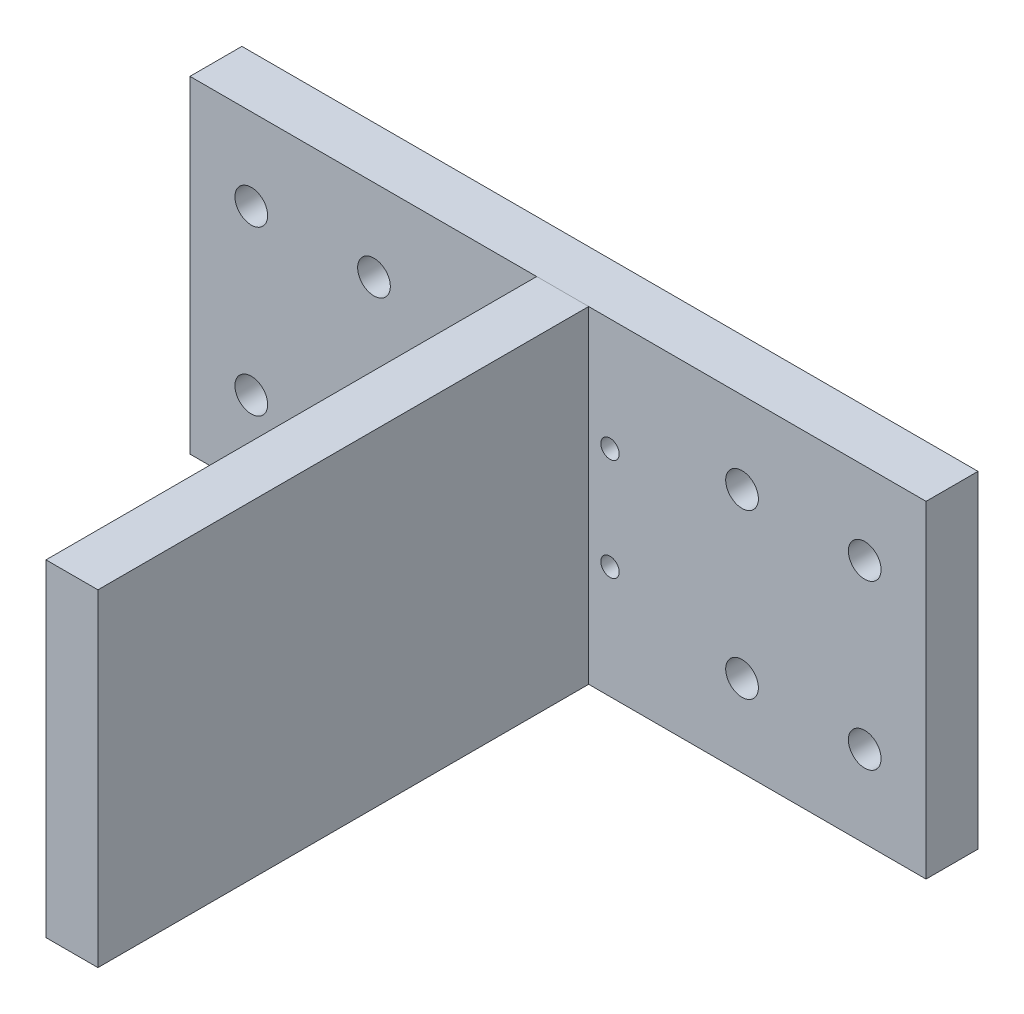
SolidWorks part; units mm, degrees
ref_plane "Alzado" through (0, 0, 0) normal (0, 0, 1) x (1, 0, 0)
ref_plane "Planta" through (0, 0, 0) normal (0, 1, 0) x (1, 0, 0)
ref_plane "Vista lateral" through (0, 0, 0) normal (1, 0, 0) x (0, 0, -1)
sketch "Croquis1" plane through (0, 0, 0) normal (0, 0, 1) x (1, 0, 0)
  line L1 (30, 0) -> (-150, 0)
  line L2 (30, 0) -> (30, 80)
  line L3 (30, 80) -> (-150, 80)
  line L4 (-150, 0) -> (-150, 80)
  circle A0 centre (-47.2885, 27.5) radius 2.25 construction
  circle A1 centre (-47.2885, 52.5) radius 2.25 construction
  circle A2 centre (-72.2885, 52.5) radius 2.25 construction
  circle A3 centre (-72.2885, 27.5) radius 2.25 construction
  circle A4 centre (-105, 60) radius 4 construction
  circle A5 centre (-135, 60) radius 4 construction
  circle A6 centre (-135, 20) radius 4 construction
  circle A7 centre (-105, 20) radius 4 construction
  circle A8 centre (-15, 60) radius 4 construction
  circle A9 centre (15, 60) radius 4 construction
  circle A10 centre (-15, 20) radius 4 construction
  circle A11 centre (15, 20) radius 4 construction
  circle A12 centre (-47.2885, 27.5) radius 2.25
  circle A13 centre (-47.2885, 52.5) radius 2.25
  circle A14 centre (-72.2885, 52.5) radius 2.25
  circle A15 centre (-72.2885, 27.5) radius 2.25
  circle A16 centre (-105, 60) radius 4
  circle A17 centre (-135, 60) radius 4
  circle A18 centre (-135, 20) radius 4
  circle A19 centre (-105, 20) radius 4
  circle A20 centre (-15, 60) radius 4
  circle A21 centre (15, 60) radius 4
  circle A22 centre (-15, 20) radius 4
  circle A23 centre (15, 20) radius 4
  dimension "D1" = 80
  dimension "D2" = 180
extrude "Saliente-Extruir1" add sketch "Croquis1" along normal blind 12.7 contours L4 L1 L2 L3 A23 A22 A21 A20 A19 A18 A17 A16 A15 A14 A13 A12
sketch "Croquis2" plane through (0, 0, 12.7) normal (0, 0, 1) x (1, 0, 0)
  line L0 (30, 0) -> (-150, 0) construction
  line L1 (-65.2, 80.0112) -> (-52.5, 80.0112)
  line L2 (-65.2, 80.0112) -> (-65.2, 0)
  line L3 (-65.2, 0) -> (-52.5, 0)
  line L4 (-52.5, 80.0112) -> (-52.5, 0)
  line L5 (-65.2, 80.0112) -> (-52.5, 0) construction
  line L6 (-65.2, 0) -> (-52.5, 80.0112) construction
  line L7 (-52.5, -8.818) -> (-52.5, -38.818) construction
  point P0 (-58.85, 40.0056)
  dimension "D1" = 80.0112
  dimension "D2" = 12.7
extrude "Saliente-Extruir2" add sketch "Croquis2" along normal blind 120
